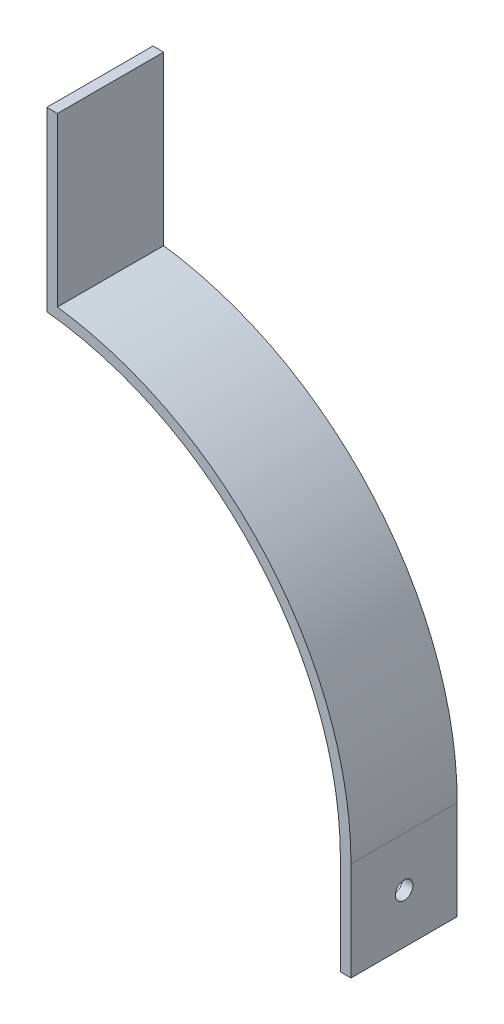
SolidWorks part; units mm, degrees
material "1060 Alloy"
ref_plane "Front Plane" through (0, 0, 0) normal (0, 0, 1) x (1, 0, 0)
ref_plane "Top Plane" through (0, 0, 0) normal (0, 1, 0) x (1, 0, 0)
ref_plane "Right Plane" through (0, 0, 0) normal (1, 0, 0) x (0, 0, -1)
sketch "Sketch1" plane through (0, 0, 0) normal (0, 0, 1) x (1, 0, 0)
  line L0 (0, 50) -> (0, 0)
  line L1 (0, 50) -> (3, 50)
  line L2 (82.9211, -92.1155) -> (82.9211, -120)
  line L3 (82.9211, -120) -> (85.9211, -120)
  line L4 (3, 50) -> (3, 2.6621)
  line L5 (85.9211, -92.1155) -> (85.9211, -120)
  line L6 (3, 50) -> (3, 51.6201) construction
  line L7 (0, 50) -> (0, 51.6201) construction
  arc A0 (85.9211, -92.1155) -> (3, 2.6621) centre (-9.7042, -92.1155) ccw
  arc A1 (82.9211, -92.1155) -> (0, 0) centre (-9.7042, -92.1155) ccw
  point P3 (79.0421, -77.7375)
  point P6 (44.214, -66.1145)
  point P15 (86.9211, -92.1155)
  dimension "D1" = 50
  dimension "D2" = 120
  dimension "D3" = 3
extrude "Boss-Extrude1" add sketch "Sketch1" along normal blind 30
sketch "Sketch2" plane through (85.9211, 0, 0) normal (1, 0, 0) x (0, 0, -1)
  line L4 (0, -120) -> (0, -92.1155)
  line L5 (0, -92.1155) -> (-30, -92.1155)
  line L6 (-30, -92.1155) -> (-30, -120)
  line L7 (-30, -120) -> (0, -120)
  line L8 (0, -120) -> (0, -92.1155) construction
  line L9 (0, -92.1155) -> (-30, -92.1155) construction
  line L10 (-30, -92.1155) -> (-30, -120) construction
  line L11 (-30, -120) -> (0, -120) construction
  circle A0 centre (-15, -106.0578) radius 2.5
  point P2 (0, 0)
  point P5 (-15, -92.1155)
  point P7 (0, 0)
  point P9 (-30, -106.0578)
  dimension "D2" = 5
  dimension "D1" = 0
extrude "Cut-Extrude1" cut sketch "Sketch2" against normal blind 30
